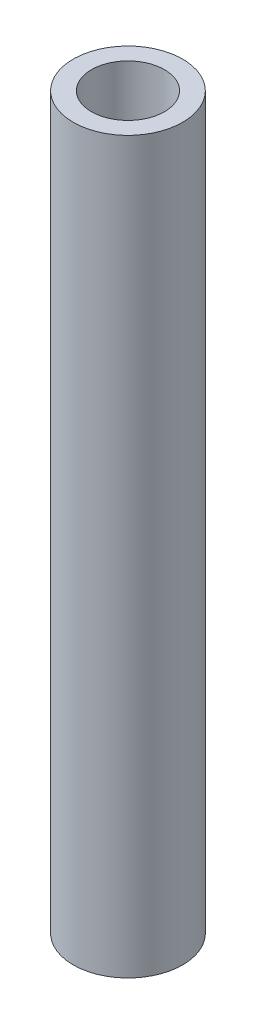
SolidWorks part; units mm, degrees
ref_plane "Front Plane" through (0, 0, 0) normal (0, 0, 1) x (1, 0, 0)
ref_plane "Top Plane" through (0, 0, 0) normal (0, 1, 0) x (1, 0, 0)
ref_plane "Right Plane" through (0, 0, 0) normal (1, 0, 0) x (0, 0, -1)
sketch "Sketch1" plane through (0, 0, 0) normal (0, 1, 0) x (1, 0, 0)
  circle A0 centre (0, 0) radius 9.525
  circle A1 centre (0, 0) radius 6.35
  dimension "D1" = 19.05
  dimension "D2" = 3.175
extrude "Boss-Extrude2" add sketch "Sketch1" along normal blind 127
